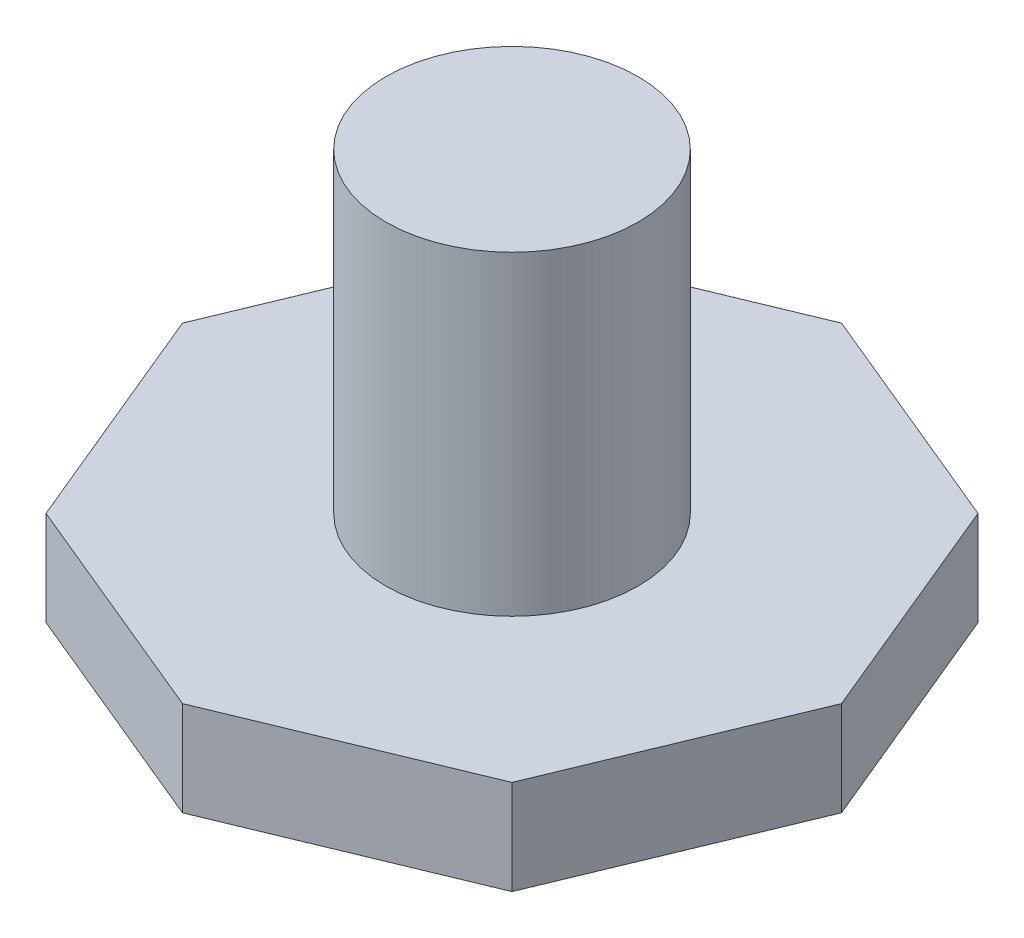
SolidWorks part; units mm, degrees
ref_plane "前视基准面" through (0, 0, 0) normal (0, 0, 1) x (1, 0, 0)
ref_plane "上视基准面" through (0, 0, 0) normal (0, 1, 0) x (1, 0, 0)
ref_plane "右视基准面" through (0, 0, 0) normal (1, 0, 0) x (0, 0, -1)
other "Configuration Table"
sketch "草图1" plane through (0, 0, 0) normal (0, 1, 0) x (1, 0, 0)
  line L1 (5.2263, 0) -> (3.6955, 3.6955)
  line L2 (3.6955, 3.6955) -> (0, 5.2263)
  line L3 (0, 5.2263) -> (-3.6955, 3.6955)
  line L4 (-3.6955, 3.6955) -> (-5.2263, 0)
  line L5 (-5.2263, 0) -> (-3.6955, -3.6955)
  line L6 (-3.6955, -3.6955) -> (0, -5.2263)
  line L7 (0, -5.2263) -> (3.6955, -3.6955)
  line L8 (3.6955, -3.6955) -> (5.2263, 0)
  circle A0 centre (0, 0) radius 4.8284 construction
  dimension "D1" = 4
extrude "凸台-拉伸1" add sketch "草图1" along normal blind 1.5
sketch "草图2" plane through (0, 1.5, 0) normal (0, 1, 0) x (1, 0, 0)
  circle A0 centre (0, 0) radius 2
  dimension "D1" = 4
extrude "凸台-拉伸2" add sketch "草图2" along normal blind 5
